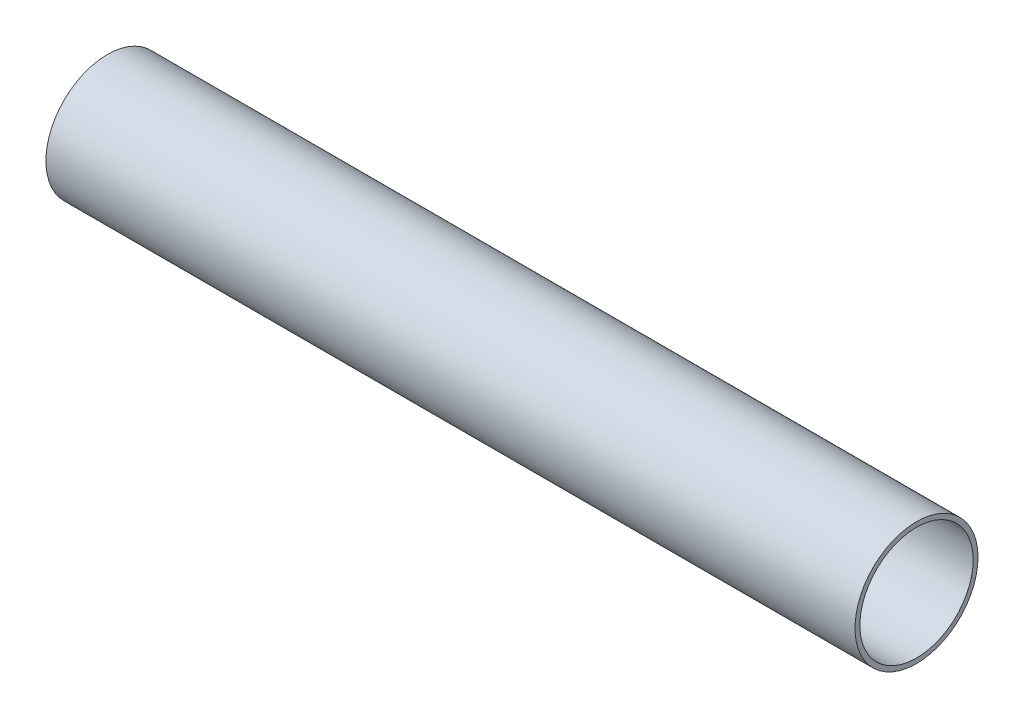
SolidWorks part; units mm, degrees
material "PVC 0.007 Plastificado"
ref_plane "Front" through (0, 0, 0) normal (0, 0, 1) x (1, 0, 0)
ref_plane "Top" through (0, 0, 0) normal (0, 1, 0) x (1, 0, 0)
ref_plane "Right" through (0, 0, 0) normal (1, 0, 0) x (0, 0, -1)
sketch "Croquis1" plane through (0, 0, 0) normal (1, 0, 0) x (0, 0, -1)
  circle A0 centre (0, 0) radius 57
  circle A1 centre (0, 0) radius 52.5
  dimension "D1" = 114
extrude "Saliente-Extruir1" add sketch "Croquis1" along normal blind 750
